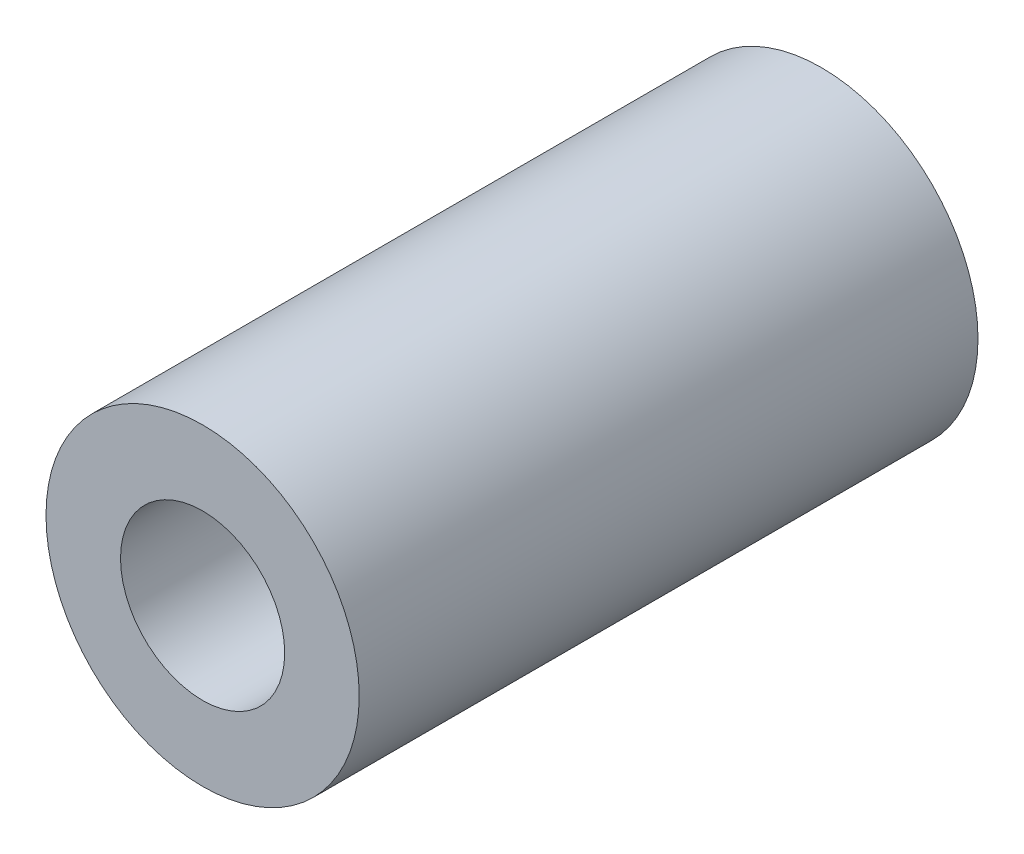
SolidWorks part; units mm, degrees
material "6061-T6 (SS)"
ref_plane "Front Plane" through (0, 0, 0) normal (0, 0, 1) x (1, 0, 0)
ref_plane "Top Plane" through (0, 0, 0) normal (0, 1, 0) x (1, 0, 0)
ref_plane "Right Plane" through (0, 0, 0) normal (1, 0, 0) x (0, 0, -1)
sketch "Sketch1" plane through (0, 0, 0) normal (0, 0, 1) x (1, 0, 0)
  circle A0 centre (0, 0) radius 1.5748
  circle A1 centre (0, 0) radius 1.5748
  circle A2 centre (0, 0) radius 0.8255
  dimension "D1" = 3.1496
  dimension "D2" = 1.651
extrude "Extrude1" add sketch "Sketch1" along normal blind 6.223 contours A0 A2
